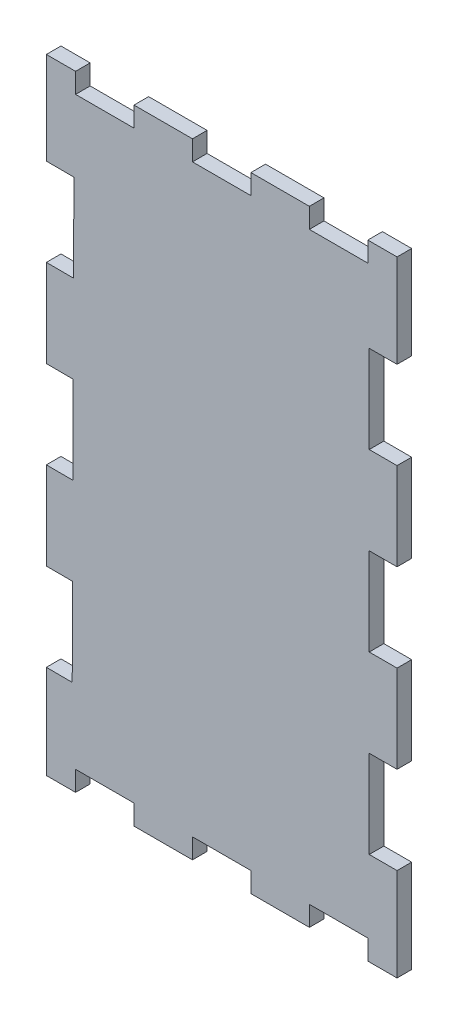
SolidWorks part; units mm, degrees
ref_plane "Front Plane" through (0, 0, 0) normal (0, 0, 1) x (1, 0, 0)
ref_plane "Top Plane" through (0, 0, 0) normal (0, 1, 0) x (1, 0, 0)
ref_plane "Right Plane" through (0, 0, 0) normal (1, 0, 0) x (0, 0, -1)
sketch "Sketch1" plane through (0, 0, 0) normal (0, 0, 1) x (1, 0, 0)
  line L1 (-38.1, -67.8434) -> (38.1, -67.8434)
  line L2 (-38.1, -67.8434) -> (-38.1, 67.8434)
  line L3 (-38.1, 67.8434) -> (38.1, 67.8434)
  line L4 (38.1, -67.8434) -> (38.1, 67.8434)
  line L5 (-38.1, -67.8434) -> (38.1, 67.8434) construction
  line L6 (-38.1, 67.8434) -> (38.1, -67.8434) construction
  point P0 (0, 0)
  dimension "D1" = 135.6868
  dimension "D2" = 76.2
extrude "Boss-Extrude1" add sketch "Sketch1" along normal blind 3.175
sketch "Sketch2" plane through (0, 0, 3.175) normal (0, 0, 1) x (1, 0, 0)
  line L0 (38.1, 67.8434) -> (-38.1, 67.8434) construction
  line L1 (-6.35, 63.5) -> (6.35, 63.5)
  line L2 (-6.35, 63.5) -> (-6.35, 72.1868)
  line L3 (-6.35, 72.1868) -> (6.35, 72.1868)
  line L4 (6.35, 63.5) -> (6.35, 72.1868)
  line L5 (-6.35, 63.5) -> (6.35, 72.1868) construction
  line L6 (-6.35, 72.1868) -> (6.35, 63.5) construction
  line L7 (-31.75, 72.1868) -> (-19.05, 72.1868)
  line L8 (-19.05, 63.5) -> (-19.05, 72.1868)
  line L9 (-31.75, 63.5) -> (-19.05, 63.5)
  line L10 (-31.75, 63.5) -> (-31.75, 72.1868)
  line L11 (0, 67.8434) -> (0, 0) construction
  line L12 (31.75, 63.5) -> (31.75, 72.1868)
  line L13 (31.75, 63.5) -> (19.05, 63.5)
  line L14 (19.05, 63.5) -> (19.05, 72.1868)
  line L15 (31.75, 72.1868) -> (19.05, 72.1868)
  line L16 (0, 0) -> (38.1, 0) construction
  line L17 (38.1, -67.8434) -> (38.1, 67.8434) construction
  line L18 (-6.35, -72.1868) -> (6.35, -63.5) construction
  line L19 (-6.35, -63.5) -> (6.35, -72.1868) construction
  line L20 (31.75, -72.1868) -> (19.05, -72.1868)
  line L21 (19.05, -63.5) -> (19.05, -72.1868)
  line L22 (31.75, -63.5) -> (19.05, -63.5)
  line L23 (31.75, -63.5) -> (31.75, -72.1868)
  line L24 (-31.75, -63.5) -> (-31.75, -72.1868)
  line L25 (-31.75, -63.5) -> (-19.05, -63.5)
  line L26 (-19.05, -63.5) -> (-19.05, -72.1868)
  line L27 (-31.75, -72.1868) -> (-19.05, -72.1868)
  line L28 (6.35, -63.5) -> (6.35, -72.1868)
  line L29 (-6.35, -72.1868) -> (6.35, -72.1868)
  line L30 (-6.35, -63.5) -> (-6.35, -72.1868)
  line L31 (-6.35, -63.5) -> (6.35, -63.5)
  point P0 (0, 67.8434)
  point P33 (0, -67.8434)
  dimension "D1" = 12.7
  dimension "D2" = 8.6868
  dimension "D3" = 2
extrude "Cut-Extrude1" cut sketch "Sketch2" against normal through all
sketch "Sketch3" plane through (0, 0, 3.175) normal (0, 0, 1) x (1, 0, 0)
  line L0 (38.1, -67.8434) -> (38.1, 67.8434) construction
  line L1 (44.1452, -9.525) -> (32.0548, -9.525)
  line L2 (44.1452, -9.525) -> (44.1452, 9.525)
  line L3 (44.1452, 9.525) -> (32.0548, 9.525)
  line L4 (32.0548, -9.525) -> (32.0548, 9.525)
  line L5 (44.1452, -9.525) -> (32.0548, 9.525) construction
  line L6 (44.1452, 9.525) -> (32.0548, -9.525) construction
  line L7 (32.0548, 28.575) -> (32.0548, 47.625)
  line L8 (44.1452, 47.625) -> (32.0548, 47.625)
  line L9 (44.1452, 28.575) -> (44.1452, 47.625)
  line L10 (44.1452, 28.575) -> (32.0548, 28.575)
  line L11 (38.1, 0) -> (-38.342, 0) construction
  line L12 (-38.342, 0) -> (0, 63.5) construction
  line L13 (-6.35, 63.5) -> (6.35, 63.5) construction
  line L14 (0, 63.5) -> (-0.121, 0) construction
  line L15 (44.1452, -28.575) -> (32.0548, -28.575)
  line L16 (44.1452, -28.575) -> (44.1452, -47.625)
  line L17 (44.1452, -47.625) -> (32.0548, -47.625)
  line L18 (32.0548, -28.575) -> (32.0548, -47.625)
  line L19 (-44.3506, 9.6936) -> (-32.3329, -9.4023) construction
  line L20 (-44.4232, -9.3562) -> (-32.2603, 9.6476) construction
  line L21 (-44.278, 28.7435) -> (-32.1877, 28.6974)
  line L22 (-44.278, 28.7435) -> (-44.2054, 47.7934)
  line L23 (-44.2054, 47.7934) -> (-32.1151, 47.7473)
  line L24 (-32.1877, 28.6974) -> (-32.1151, 47.7473)
  line L25 (-32.3329, -9.4023) -> (-32.2603, 9.6476)
  line L26 (-44.3506, 9.6936) -> (-32.2603, 9.6476)
  line L27 (-44.4232, -9.3562) -> (-44.3506, 9.6936)
  line L28 (-44.4232, -9.3562) -> (-32.3329, -9.4023)
  line L29 (-32.4055, -28.4522) -> (-32.4781, -47.502)
  line L30 (-44.5684, -47.4559) -> (-32.4781, -47.502)
  line L31 (-44.4958, -28.4061) -> (-44.5684, -47.4559)
  line L32 (-44.4958, -28.4061) -> (-32.4055, -28.4522)
  point P0 (38.1, 0)
  point P30 (-38.3417, 0.1457)
  dimension "D1" = 19.05
  dimension "D2" = 12.0904
  dimension "D3" = 2
extrude "Cut-Extrude2" cut sketch "Sketch3" against normal through all
